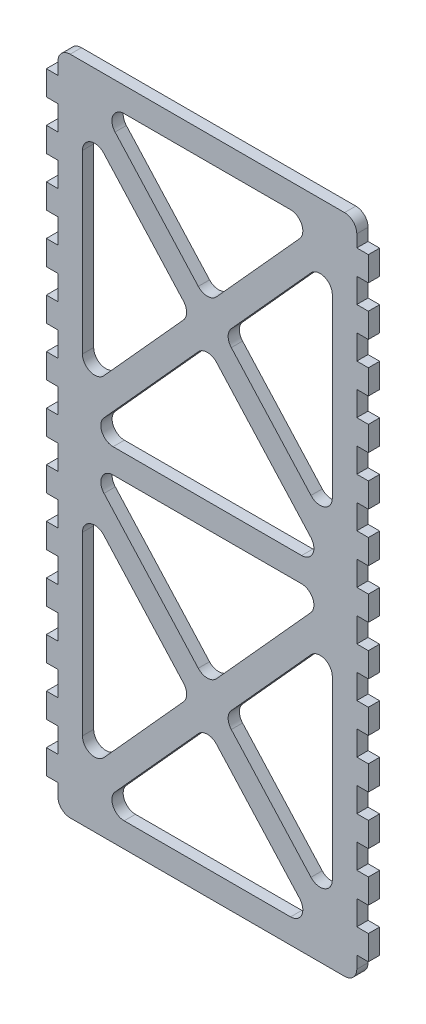
SolidWorks part; units mm, degrees
ref_plane "Front Plane" through (0, 0, 0) normal (0, 0, 1) x (1, 0, 0)
ref_plane "Top Plane" through (0, 0, 0) normal (0, 1, 0) x (1, 0, 0)
ref_plane "Right Plane" through (0, 0, 0) normal (1, 0, 0) x (0, 0, -1)
sketch "Sketch1" plane through (0, 0, 0) normal (0, 0, 1) x (1, 0, 0)
  line L1 (-38.735, 85.725) -> (38.735, 85.725)
  line L2 (-38.735, 85.725) -> (-38.735, -85.725)
  line L3 (-38.735, -85.725) -> (38.735, -85.725)
  line L4 (38.735, 85.725) -> (38.735, -85.725)
  point P4 (0, 85.725)
  point P6 (-38.735, 0)
  dimension "D1" = 77.47
  dimension "D2" = 171.45
extrude "Boss-Extrude1" add sketch "Sketch1" along normal mid plane 2.921
ref_plane "Plane1" through (0, 0, 0) normal (-1, 0, 0) x (0, 0, 1)
sketch "Sketch3" plane through (-38.735, 0, 0) normal (-1, 0, 0) x (0, 0, 1)
  line L0 (-1.4605, 85.725) -> (-1.4605, -85.725) construction
  line L1 (-1.4605, -79.375) -> (1.4605, -79.375)
  line L2 (-1.4605, -79.375) -> (-1.4605, -73.025)
  line L3 (-1.4605, -73.025) -> (1.4605, -73.025)
  line L4 (1.4605, -79.375) -> (1.4605, -73.025)
  line L5 (1.4605, 85.725) -> (1.4605, -85.725) construction
  line L6 (1.4605, -85.725) -> (-1.4605, -85.725) construction
  dimension "D1" = 6.35
  dimension "D2" = 6.35
extrude "Boss-Extrude2" add sketch "Sketch3" along normal blind 3
pattern_linear "LPattern1" count 13 spacing 12.7 along (0, 1, 0) of "Boss-Extrude2"
mirror "Mirror1" about plane through (0, 0, 0) normal (-1, 0, 0) of "LPattern1", "Boss-Extrude2"
sketch "Sketch4" plane through (0, 0, 1.4605) normal (0, 0, 1) x (1, 0, 0)
  line L0 (38.735, 0) -> (-38.735, -85.725) construction
  line L1 (-38.735, 0) -> (38.735, 0) construction
  line L2 (-38.735, 85.725) -> (38.735, 85.725) construction
  line L3 (-38.735, 85.725) -> (-38.735, -85.725) construction
  line L4 (-38.735, -85.725) -> (38.735, -85.725) construction
  line L5 (38.735, 85.725) -> (38.735, -85.725) construction
  line L6 (38.735, 0) -> (-38.735, 85.725) construction
  line L7 (38.735, 85.725) -> (-38.735, 0) construction
  line L8 (36.3794, 87.8538) -> (-43.0144, 0)
  line L9 (-43.0144, 0) -> (36.3794, -87.8538)
  line L10 (43.0144, 0) -> (-36.3794, -87.8538)
  line L11 (43.0144, 0) -> (-36.3794, 87.8538)
  line L12 (41.0906, 83.5962) -> (-34.4556, 0)
  line L13 (-34.4556, 0) -> (41.0906, -83.5962)
  line L14 (34.4556, 0) -> (-41.0906, -83.5962)
  line L15 (34.4556, 0) -> (-41.0906, 83.5962)
  line L114 (-32.385, 79.375) -> (-32.385, -79.375)
  line L115 (-32.385, -79.375) -> (32.385, -79.375)
  line L116 (32.385, 79.375) -> (32.385, -79.375)
  line L117 (-32.385, 79.375) -> (32.385, 79.375)
  line L118 (-38.735, -3.175) -> (38.735, -3.175)
  line L119 (-38.735, 3.175) -> (38.735, 3.175)
  line L120 (-38.735, 0) -> (38.735, -85.725) construction
  dimension "D1" = 6.35
  dimension "D2" = 3.175
  dimension "D3" = 3.175
  dimension "D4" = 3.175
  dimension "D5" = 3.175
extrude "Cut-Extrude1" cut sketch "Sketch4" against normal through all contours L117 L11 L8 | L15 L114 L8 | L116 L12 L11 | L12 L119 L15 | L118 L13 L14 | L9 L114 L14 | L10 L115 L9 | L116 L10 L13
fillet "Fillet1" radius 3.175 24 edges at (-32.385, 11.762, 0) (-32.385, -11.762, 0) (-28.7171, -79.375, 0) (28.7171, -79.375, 0) (32.385, -11.762, 0) (32.385, -73.963, 0) (4.2794, -42.8625, 0) (-32.385, -73.963, 0) (-4.2794, -42.8625, 0) (0, -47.5979, 0) (0, -38.1271, 0) (31.5863, -3.175, 0) (-31.5863, -3.175, 0) (-31.5863, 3.175, 0) (0, 38.1271, 0) (-4.2794, 42.8625, 0) (31.5863, 3.175, 0) (32.385, 11.762, 0) (32.385, 73.963, 0) (4.2794, 42.8625, 0) (0, 47.5979, 0) (28.7171, 79.375, 0) (-28.7171, 79.375, 0) (-32.385, 73.963, 0)
fillet "Fillet2" radius 3.175 4 edges at (38.735, -85.725, 0) (38.735, 85.725, 0) (-38.735, 85.725, 0) (-38.735, -85.725, 0)
